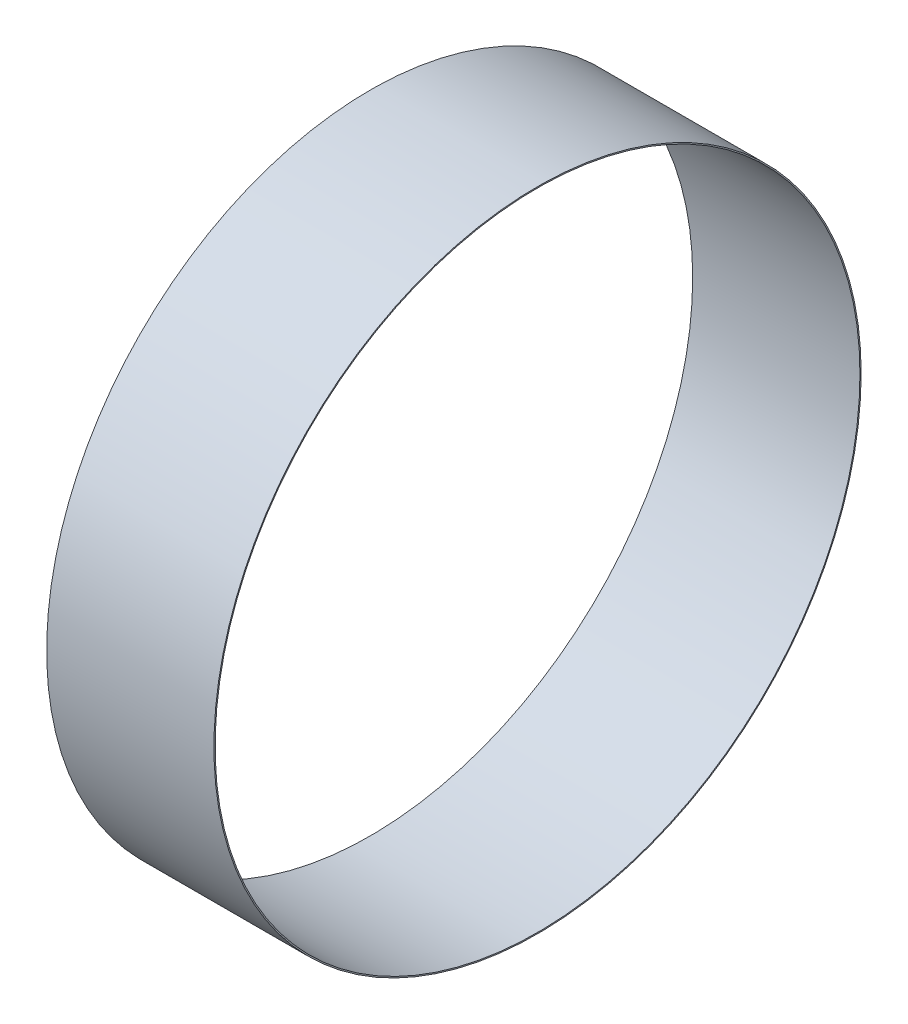
SolidWorks part; units mm, degrees
material "1023 Carbon Steel Sheet (SS)"
ref_plane "Front Plane" through (0, 0, 0) normal (0, 0, 1) x (1, 0, 0)
ref_plane "Top Plane" through (0, 0, 0) normal (0, 1, 0) x (1, 0, 0)
ref_plane "Right Plane" through (0, 0, 0) normal (1, 0, 0) x (0, 0, -1)
sketch "Sketch1" plane through (0, 0, 0) normal (1, 0, 0) x (0, 0, -1)
  circle A0 centre (0, 0) radius 803
  circle A1 centre (0, 0) radius 800
  dimension "D1" = 1600
  dimension "D2" = 1606
extrude "Boss-Extrude1" add sketch "Sketch1" along normal blind 415
